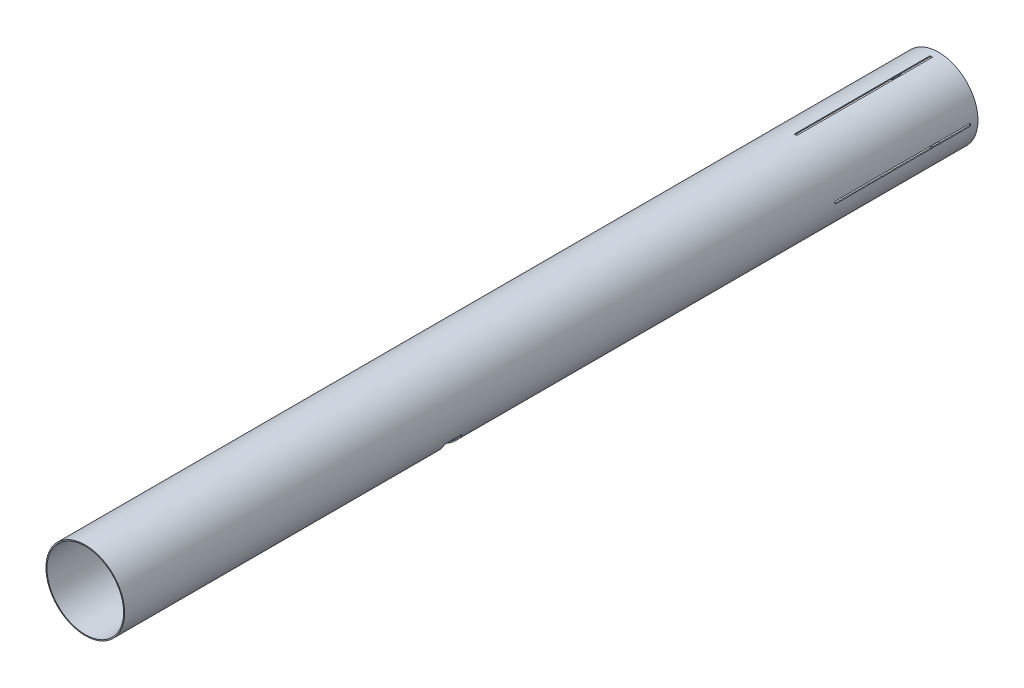
SolidWorks part; units mm, degrees
material "E-Glass Fiber"
ref_plane "Front" through (0, 0, 0) normal (0, 0, 1) x (1, 0, 0)
ref_plane "Top" through (0, 0, 0) normal (0, 1, 0) x (1, 0, 0)
ref_plane "Right" through (0, 0, 0) normal (1, 0, 0) x (0, 0, -1)
sketch "Sketch1" plane through (0, 0, 0) normal (0, 0, 1) x (1, 0, 0)
  circle A0 centre (0, 0) radius 78.35
  circle A1 centre (0, 0) radius 76.35
  dimension "D1" = 2
  dimension "D2" = 152.7
extrude "Boss-Extrude1" add sketch "Sketch1" along normal blind 1700
sketch "Sketch4" plane through (0, 0, 0) normal (0, 0, 1) x (1, 0, 0)
  line L0 (0, 0) -> (25.0476, -25.0476) construction
  line L1 (0, 0) -> (0, -24.8691) construction
  dimension "D1" = 45
ref_plane "Plane1" through (0, 0, 0) normal (0.7071, -0.7071, 0) x (0, 0, -1)
sketch "Sketch5" plane through (0, 0, 0) normal (0.7071, -0.7071, 0) x (0, 0, -1)
  line L0 (0, -78.35) -> (0, 78.35) construction
  circle A0 centre (-1034.89, 0) radius 15
  dimension "D1" = 30
  dimension "D2" = 1034.89
extrude "Cut-Extrude2" cut sketch "Sketch5" along normal through all
sketch "Sketch6" plane through (0, 0, 0) normal (0, 1, 0) x (1, 0, 0)
  line L0 (-2.4, -285) -> (-2.4, -15)
  line L1 (-2.4, -285) -> (2.4, -285)
  line L2 (-2.4, -15) -> (2.4, -15)
  line L3 (2.4, -285) -> (2.4, -15)
  line L4 (-2.4, -285) -> (2.4, -15) construction
  line L5 (-2.4, -15) -> (2.4, -285) construction
  line L6 (78.35, 0) -> (-78.35, 0) construction
  line L7 (0, 0) -> (0, -1700) construction
  line L8 (-78.35, -1700) -> (78.35, -1700) construction
  point P1 (0, -150)
  dimension "D1" = 15
  dimension "D2" = 4.8
  dimension "D3" = 270
extrude "Cut-Extrude3" cut sketch "Sketch6" against normal through all both and the other way through all
pattern_circular "CirPattern1" count 2 every 90 about axis through (0, 0, 0) along (0, 0, 1) of "Cut-Extrude3"
ref_plane "Plane2" through (0, 0, 1035) normal (0, 0, 1) x (1, 0, 0)
sketch "Sketch7" plane through (0, 0, 1035) normal (0, 0, 1) x (1, 0, 0)
  line L0 (37.9692, -68.5351) -> (37, -66.7856)
  line L1 (66.9165, -36.7628) -> (68.6694, -37.7258)
  line L2 (0, 0) -> (55.5, -55.3035) construction
  line L3 (39.5296, -65.3202) -> (40.5651, -67.0313)
  line L4 (65.4601, -39.2976) -> (67.1748, -40.327)
  arc A0 (68.6694, -37.7258) -> (37.9692, -68.5351) centre (0, 0) cw
  circle A2 centre (0, 0) radius 78.35 construction
  arc A3 (66.9165, -36.7628) -> (37, -66.7856) centre (0, 0) cw
  circle A4 centre (0, 0) radius 76.35 construction
  arc A5 (43.7704, -64.9836) -> (64.9836, -43.7704) centre (0, 0) ccw construction
  point P18 (36.8904, -66.8463)
  point P19 (68.2355, -34.2525)
  dimension "D1" = 55.5
  dimension "D2" = 2
  dimension "D6" = 37
  dimension "D3" = 2
  dimension "D4" = 3
  dimension "D5" = 3
extrude "Cut-Extrude4" cut sketch "Sketch7" against normal blind 17.5 and the other way blind 17.5 contours L1 A3 L4 A0 | L3 A3 L0 A0 | L2 A3 L3 A0 | A3 L2 A0 L4
